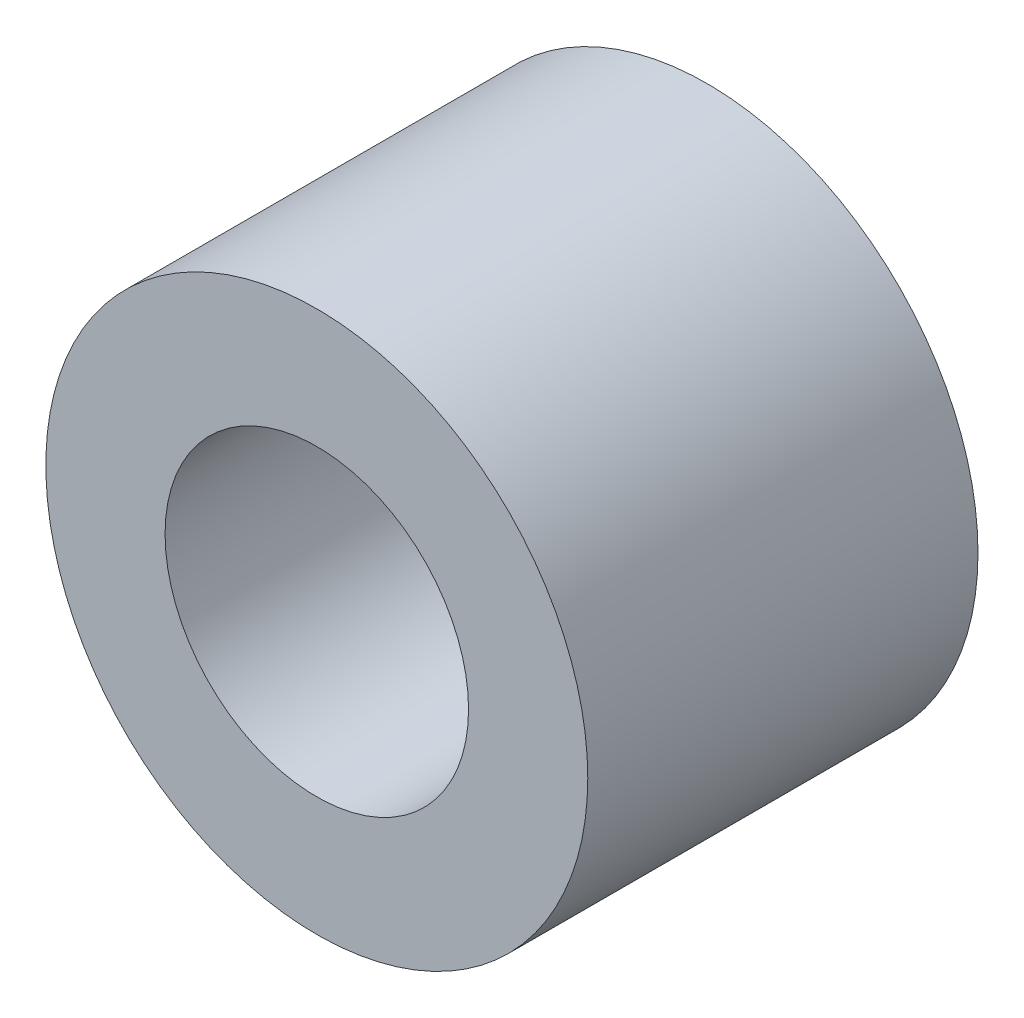
SolidWorks part; units mm, degrees
material "Delrin 2700 NC010, Low Viscosity Acetal Copolymer (SS)"
ref_plane "Front Plane" through (0, 0, 0) normal (0, 0, 1) x (1, 0, 0)
ref_plane "Top Plane" through (0, 0, 0) normal (0, 1, 0) x (1, 0, 0)
ref_plane "Right Plane" through (0, 0, 0) normal (1, 0, 0) x (0, 0, -1)
sketch "Sketch1" plane through (0, 0, 0) normal (0, 0, 1) x (1, 0, 0)
  circle A0 centre (0, 0) radius 4.8895
  circle A1 centre (0, 0) radius 8.7312
  dimension "D1" = 9.779
  dimension "D2" = 17.4625
extrude "Boss-Extrude1" add sketch "Sketch1" along normal blind 12.573
equation "\"D1@Boss-Extrude1\"=0.500-.005"
equation "\"D2@Sketch1\"=11/16"
